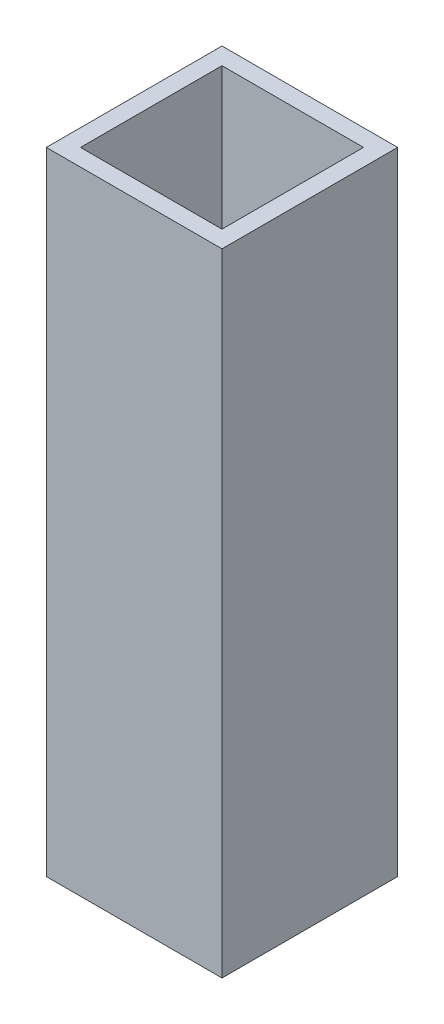
SolidWorks part; units mm, degrees
ref_plane "Front Plane" through (0, 0, 0) normal (0, 0, 1) x (1, 0, 0)
ref_plane "Top Plane" through (0, 0, 0) normal (0, 1, 0) x (1, 0, 0)
ref_plane "Right Plane" through (0, 0, 0) normal (1, 0, 0) x (0, 0, -1)
sketch "Sketch1" plane through (0, 0, 0) normal (0, 1, 0) x (1, 0, 0)
  line L1 (-6.175, -6.175) -> (6.175, -6.175)
  line L2 (-6.175, -6.175) -> (-6.175, 6.175)
  line L3 (-6.175, 6.175) -> (6.175, 6.175)
  line L4 (6.175, -6.175) -> (6.175, 6.175)
  line L5 (-6.175, -6.175) -> (6.175, 6.175) construction
  line L6 (-6.175, 6.175) -> (6.175, -6.175) construction
  point P0 (0, 0)
  dimension "D1" = 12.35
extrude "Boss-Extrude1" add sketch "Sketch1" along normal blind 44.4
shell "Shell1" thickness 1.2
